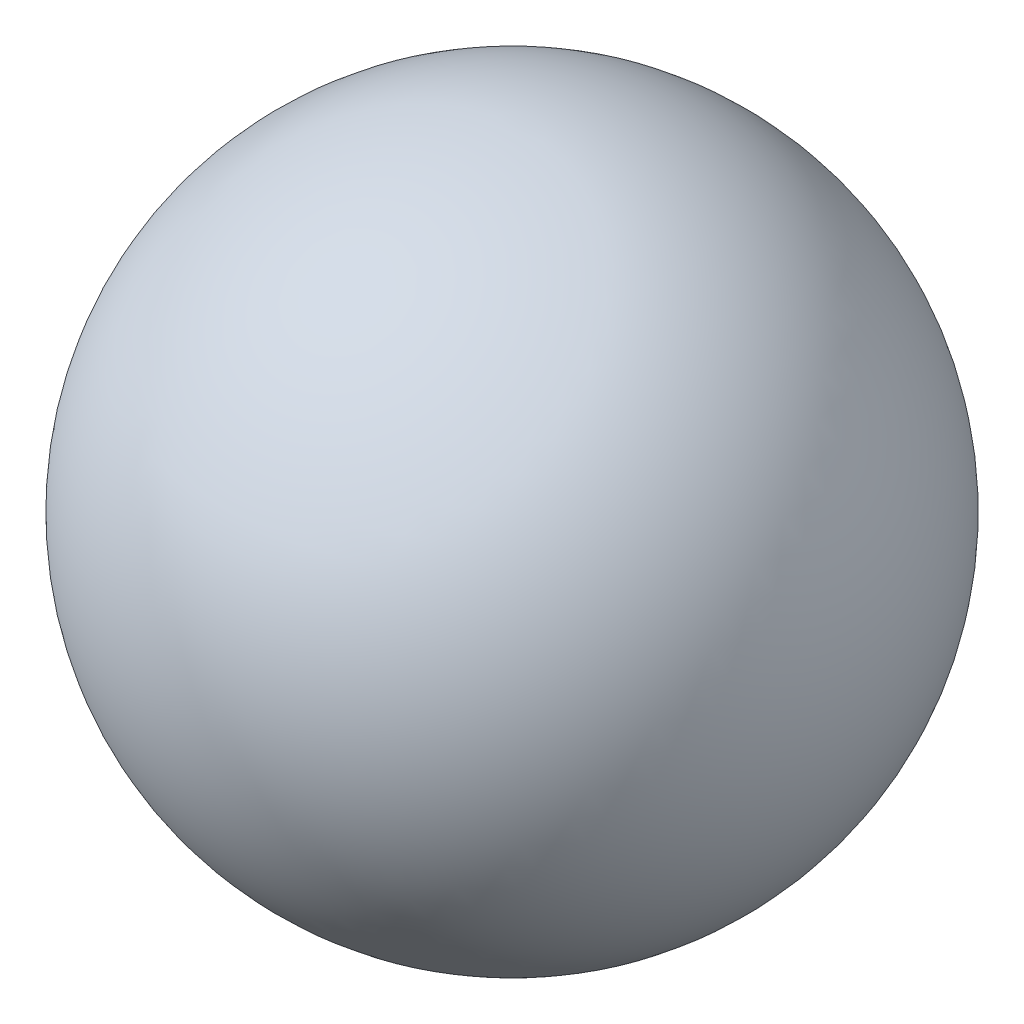
SolidWorks part; units mm, degrees
ref_plane "Front Plane" through (0, 0, 0) normal (0, 0, 1) x (1, 0, 0)
ref_plane "Top Plane" through (0, 0, 0) normal (0, 1, 0) x (1, 0, 0)
ref_plane "Right Plane" through (0, 0, 0) normal (1, 0, 0) x (0, 0, -1)
sketch "Sketch1" plane through (0, 0, 0) normal (0, 0, 1) x (1, 0, 0)
  line L0 (0, 3.1496) -> (0, 0)
  arc A0 (0, 0) -> (0, 3.1496) centre (0, 1.5748) cw
  dimension "D1" = 1.5748
revolve "Revolve1" add sketch "Sketch1" angle 360 about L0
